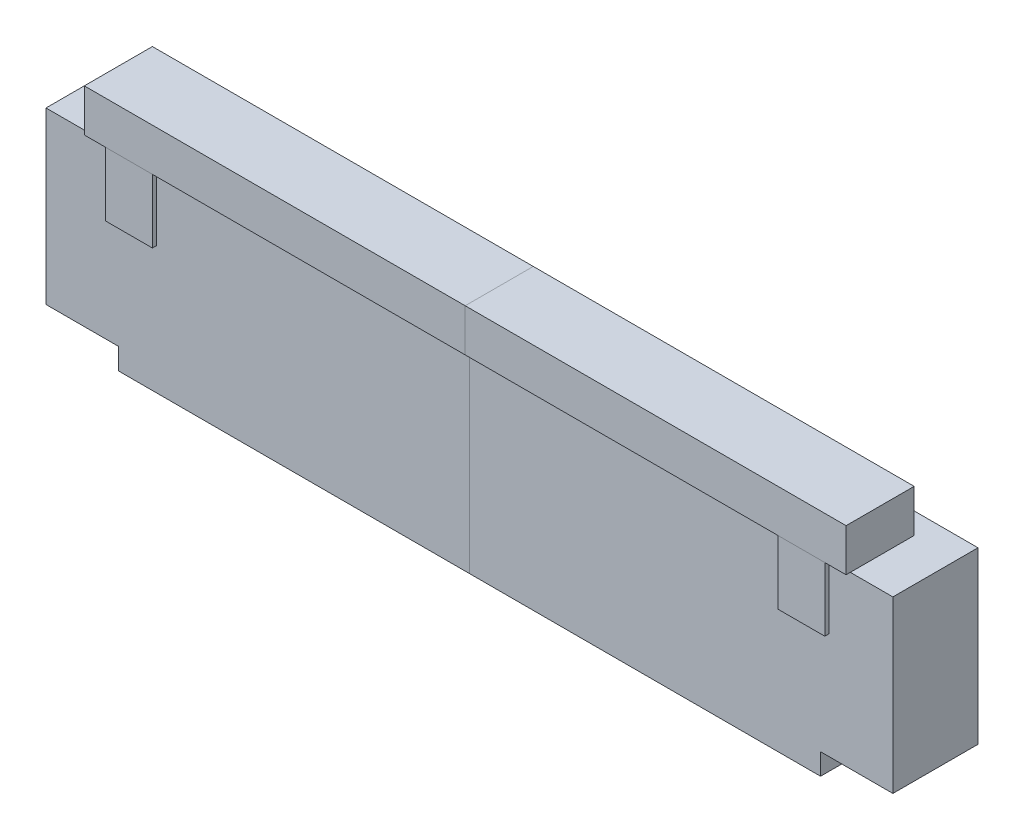
SolidWorks part; units mm, degrees
other "Детальный элемент1"
ref_plane "Спереди" through (0, 0, 0) normal (0, 0, 1) x (1, 0, 0)
ref_plane "Сверху" through (0, 0, 0) normal (0, 1, 0) x (1, 0, 0)
ref_plane "Справа" through (0, 0, 0) normal (1, 0, 0) x (0, 0, -1)
sketch "Эскиз1" plane through (0, 0, 0) normal (0, 0, 1) x (1, 0, 0)
  line L1 (0, -4.5) -> (9.95, -4.5)
  line L2 (0, -4.5) -> (0, 0)
  line L3 (0, 0) -> (9.95, 0)
  line L4 (9.95, -4.5) -> (9.95, 0)
  dimension "D1" = 9.95
  dimension "D2" = 4.5
extrude "Бобышка-Вытянуть1" add sketch "Эскиз1" along normal blind 2
sketch "Эскиз3" plane through (0, -4.5, 0) normal (0, -1, 0) x (1, 0, 0)
  line L0 (0, 0) -> (9.95, 0) construction
  line L1 (9.95, 2) -> (8.25, 2)
  line L2 (9.95, 2) -> (9.95, 0.6)
  line L3 (9.95, 0.6) -> (8.25, 0.6)
  line L4 (8.25, 2) -> (8.25, 0.6)
  dimension "D1" = 1.7
  dimension "D2" = 0.6
extrude "Вырез-Вытянуть1" cut sketch "Эскиз3" against normal blind 0.5
sketch "Эскиз4" plane through (0, -4.5, 0) normal (0, -1, 0) x (1, 0, 0)
  line L0 (0, 0) -> (9.95, 0) construction
  line L1 (9.95, 0.6) -> (8.95, 0.6)
  line L2 (9.95, 0.6) -> (9.95, 0)
  line L3 (9.95, 0) -> (8.95, 0)
  line L4 (8.95, 0.6) -> (8.95, 0)
  dimension "D1" = 1
extrude "Вырез-Вытянуть2" cut sketch "Эскиз4" against normal up to surface (0.5 mm away) up to face at (9.1, -4, 1.3)
sketch "Эскиз2" plane through (0, 0, 0) normal (0, 1, 0) x (1, 0, 0)
  line L0 (9.95, -2) -> (9.95, 0) construction
  line L1 (0, -2.1) -> (8.95, -2.1)
  line L2 (0, -2.1) -> (0, -0.5)
  line L3 (0, -0.5) -> (8.95, -0.5)
  line L4 (8.95, -2.1) -> (8.95, -0.5)
  line L5 (0, -2) -> (0, 0) construction
  line L6 (9.95, -2) -> (0, -2) construction
  point P7 (0, 0)
  dimension "D1" = 1.6
  dimension "D2" = 1
  dimension "D3" = 0.1
extrude "Бобышка-Вытянуть2" add sketch "Эскиз2" along normal blind 1 separate body
sketch "Эскиз5" plane through (0, 0, 0) normal (0, -1, 0) x (1, 0, 0)
  line L0 (0, 2.1) -> (8.95, 2.1) construction
  line L1 (8.45, 2.1) -> (7.35, 2.1)
  line L2 (8.45, 2.1) -> (8.45, 0.5)
  line L3 (8.45, 0.5) -> (7.35, 0.5)
  line L4 (7.35, 2.1) -> (7.35, 0.5)
  line L5 (8.95, 0.5) -> (0, 0.5) construction
  line L6 (9.95, 2) -> (9.95, 0) construction
  dimension "D1" = 1.5
  dimension "D2" = 1.1
extrude "Бобышка-Вытянуть3" add sketch "Эскиз5" along normal blind 1.5 separate body
mirror "Зеркальное отражение1" about plane through (0, -4.5, 2) normal (1, 0, 0) of bodies 108 110 111
sketch "Эскиз7" plane through (0, -4.5, 0) normal (0, -1, 0) x (1, 0, 0)
  line L0 (0, 0) -> (8.95, 0) construction
  line L1 (6.9, 0) -> (7.1, 0)
  line L2 (6.9, 0) -> (6.9, 0.15)
  line L3 (6.9, 0.15) -> (7.1, 0.15)
  line L4 (7.1, 0) -> (7.1, 0.15)
  point P6 (7, 0)
  dimension "D1" = 0.2
  dimension "D2" = 0.15
  dimension "D3" = 7
extrude "Бобышка-Вытянуть4" add sketch "Эскиз7" along normal blind 0.7 separate body
pattern_linear "Линейный массив1" count 29 spacing 0.5 along (-1, 0, 0) of "Бобышка-Вытянуть4"
equation "\"N\"= 29"
equation "\"D3@Эскиз7\"=0.25*(\"N\"-1)"
